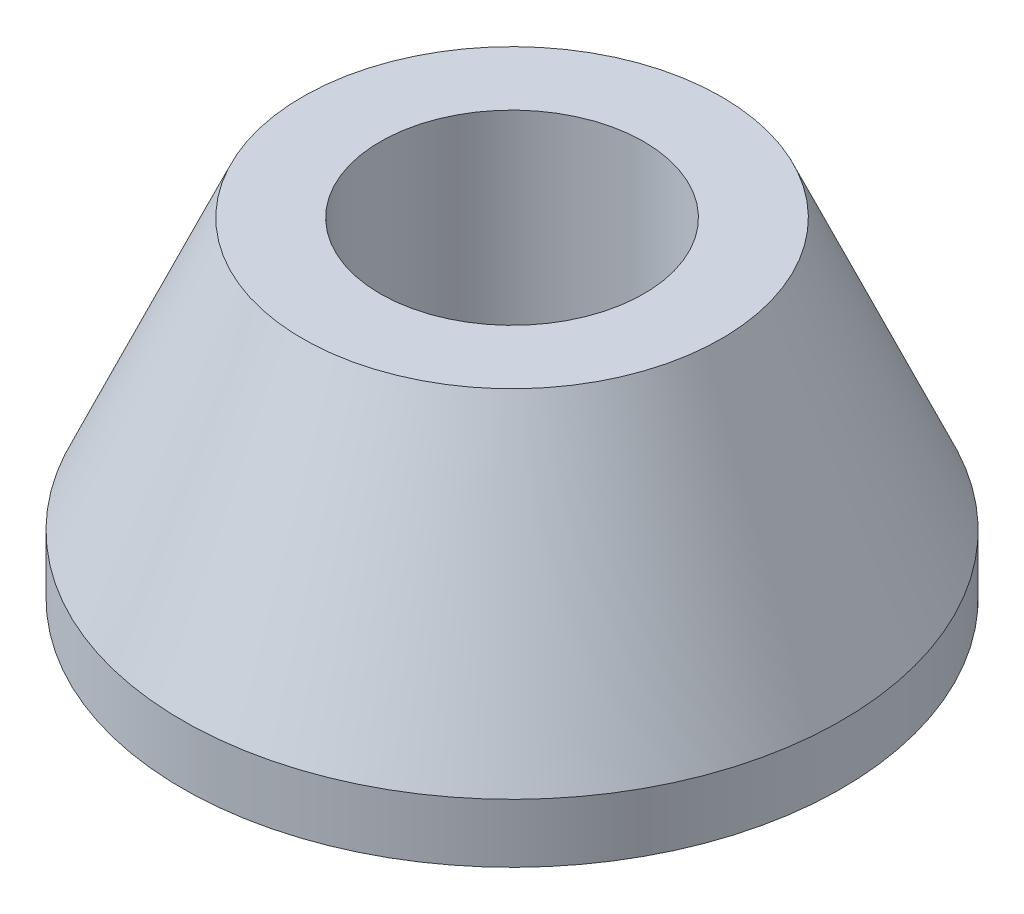
SolidWorks part; units mm, degrees
ref_plane "Front Plane" through (0, 0, 0) normal (0, 0, 1) x (1, 0, 0)
ref_plane "Top Plane" through (0, 0, 0) normal (0, 1, 0) x (1, 0, 0)
ref_plane "Right Plane" through (0, 0, 0) normal (1, 0, 0) x (0, 0, -1)
sketch "Sketch1" plane through (0, 0, 0) normal (0, 0, 1) x (1, 0, 0)
  line L0 (0, 0) -> (0, 15)
  line L1 (-2.4362, 0) -> (-15, 0)
  line L2 (-15, 0) -> (-15, 2.6798)
  line L3 (-15, 2.6798) -> (-9.536, 15)
  line L4 (-9.536, 15) -> (-6, 15)
  line L5 (-6, 15) -> (-6, 2)
  line L6 (-6, 2) -> (-2.4362, 2)
  line L7 (-2.4362, 2) -> (-2.4362, 0)
  point P5 (0, 0)
  point P11 (0, 0)
  point P12 (-9.536, 15)
  dimension "D1" = 15
  dimension "D2" = 6
  dimension "D3" = 2.4362
  dimension "D4" = 15
  dimension "D5" = 2
revolve "Revolve1" add sketch "Sketch1" angle 360 about L0
